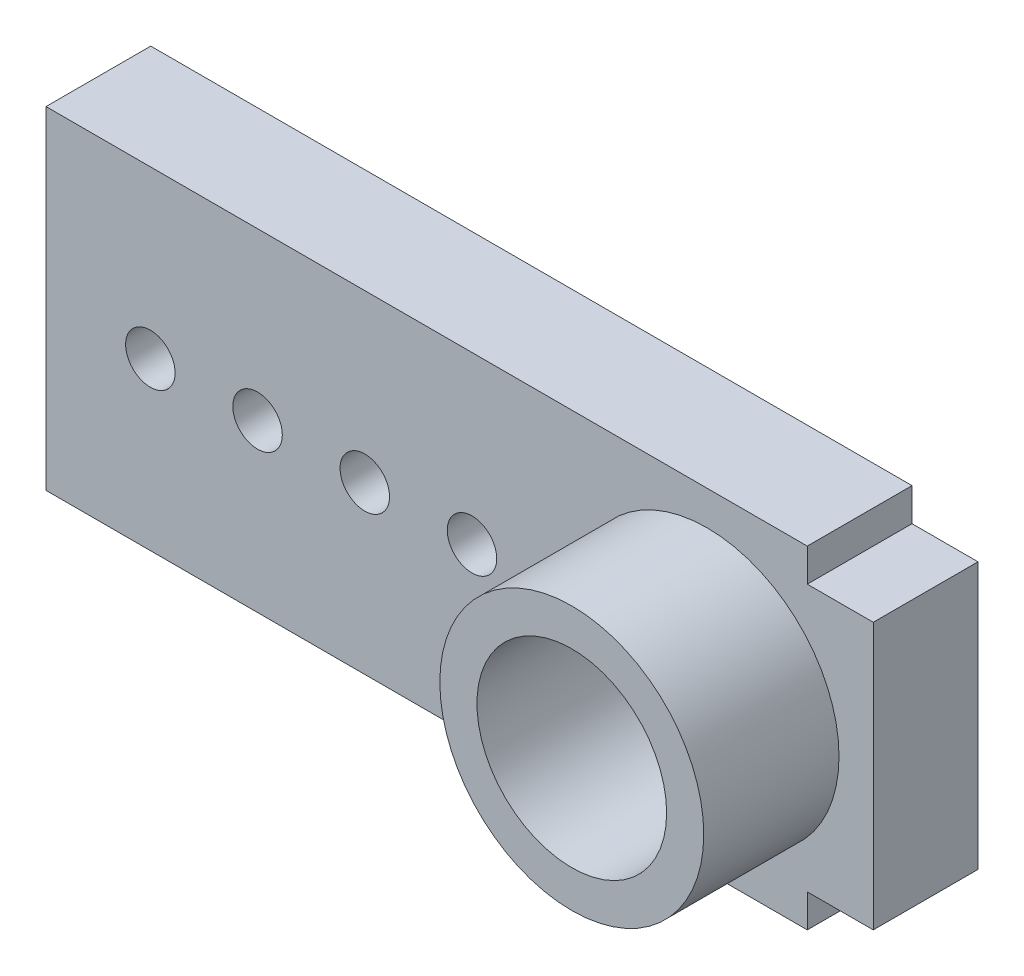
SolidWorks part; units mm, degrees
ref_plane "Front Plane" through (0, 0, 0) normal (0, 0, 1) x (1, 0, 0)
ref_plane "Top Plane" through (0, 0, 0) normal (0, 1, 0) x (1, 0, 0)
ref_plane "Right Plane" through (0, 0, 0) normal (1, 0, 0) x (0, 0, -1)
sketch "Sketch1" plane through (0, 0, 0) normal (0, 0, 1) x (1, 0, 0)
  line L0 (0, 7.125) -> (0, -7.125) construction
  line L1 (-7.125, 0) -> (7.125, 0) construction
  line L2 (0, 7.125) -> (0, 16.875) construction
  line L3 (-5.0381, 5.0381) -> (5.0381, -5.0381) construction
  line L4 (-5.0381, -5.0381) -> (5.0381, 5.0381) construction
  line L5 (-5.0381, 5.0381) -> (-5.0381, 20.0381)
  line L6 (-5.0381, 20.0381) -> (5.0381, 20.0381)
  line L7 (5.0381, 20.0381) -> (5.0381, 5.0381)
  line L8 (5.0381, 5.0381) -> (20.0381, 5.0381)
  line L9 (20.0381, 5.0381) -> (20.0381, -5.0381)
  line L10 (20.0381, -5.0381) -> (5.0381, -5.0381)
  line L11 (7.125, 0) -> (16.875, 0) construction
  line L12 (5.0381, -5.0381) -> (5.0381, -20.0381)
  line L13 (5.0381, -20.0381) -> (-5.0381, -20.0381)
  line L14 (-5.0381, -20.0381) -> (-5.0381, -5.0381)
  line L15 (0, -7.125) -> (0, -16.875) construction
  line L16 (-5.0381, -5.0381) -> (-20.0381, -5.0381)
  line L17 (-20.0381, -5.0381) -> (-20.0381, 5.0381)
  line L18 (-20.0381, 5.0381) -> (-5.0381, 5.0381)
  line L19 (-7.125, 0) -> (-16.875, 0) construction
  circle A0 centre (0, 0) radius 2.875
  circle A1 centre (0, 0) radius 7.125 construction
  circle A2 centre (0, 7.125) radius 0.75
  circle A3 centre (0, 10.375) radius 0.75
  circle A4 centre (0, 13.625) radius 0.75
  circle A5 centre (0, 16.875) radius 0.75
  circle A6 centre (7.125, 0) radius 0.75
  circle A7 centre (10.375, 0) radius 0.75
  circle A8 centre (13.625, 0) radius 0.75
  circle A9 centre (16.875, 0) radius 0.75
  circle A10 centre (0, -7.125) radius 0.75
  circle A11 centre (0, -10.375) radius 0.75
  circle A12 centre (0, -13.625) radius 0.75
  circle A13 centre (0, -16.875) radius 0.75
  circle A14 centre (-7.125, 0) radius 0.75
  circle A15 centre (-10.375, 0) radius 0.75
  circle A16 centre (-13.625, 0) radius 0.75
  circle A17 centre (-16.875, 0) radius 0.75
  point P9 (0, 10.375)
  point P11 (0, 13.625)
  point P27 (10.375, 0)
  point P29 (13.625, 0)
  point P41 (0, -10.375)
  point P43 (0, -13.625)
  point P55 (-10.375, 0)
  point P57 (-13.625, 0)
  point P67 (0, 0)
  dimension "D1" = 5.75
  dimension "D2" = 14.25
  dimension "D3" = 1.5
  dimension "D7" = 1.5
  dimension "D8" = 1.5
  dimension "D9" = 1.5
  dimension "D4" = 9.75
  dimension "D5" = 3.25
  dimension "D6" = 3.25
  dimension "D10" = 45
  dimension "D11" = 45
  dimension "D12" = 15
  dimension "D13" = 4
extrude "Boss-Extrude1" add sketch "Sketch1" along normal blind 3.175
sketch "Sketch2" plane through (0, 0, 3.175) normal (0, 0, 1) x (1, 0, 0)
  circle A0 centre (0, 0) radius 4
  circle A1 centre (0, 0) radius 2.875
  dimension "D1" = 8
  dimension "D2" = 5.75
extrude "Boss-Extrude2" add sketch "Sketch2" along normal blind 4.1
sketch "Sketch3" plane through (0, 0, 0) normal (0, 0, -1) x (-1, 0, 0)
  line L0 (-5.0381, 4.0381) -> (-5.0381, -4.0381)
  line L1 (-5.0381, 5.0381) -> (-21.0381, 5.0381)
  line L2 (-5.0381, -5.0381) -> (-21.0381, -5.0381)
  line L3 (-21.0381, 5.0381) -> (-21.0381, -5.0381)
  line L4 (-3.0381, 5.0381) -> (5.0381, 5.0381)
  line L5 (-5.0381, 5.0381) -> (-5.0381, 21.0381)
  line L6 (5.0381, 5.0381) -> (5.0381, 21.0381)
  line L7 (-5.0381, 21.0381) -> (5.0381, 21.0381)
  line L8 (-3.0381, -4.0381) -> (-3.0381, -5.0381)
  line L9 (-5.0381, -4.0381) -> (-3.0381, -4.0381)
  line L10 (-5.0381, -21.0381) -> (5.0381, -21.0381)
  line L11 (5.0381, -5.0381) -> (5.0381, -21.0381)
  line L12 (-20.0381, 0) -> (20.0381, 0) construction
  line L13 (0, 20.0381) -> (0, -20.0381) construction
  line L14 (-5.0381, 20.0381) -> (5.0381, 20.0381) construction
  line L15 (5.0381, -20.0381) -> (-5.0381, -20.0381) construction
  line L16 (-5.0381, 4.0381) -> (-3.0381, 4.0381)
  line L17 (-3.0381, 4.0381) -> (-3.0381, 5.0381)
  line L18 (-20.0381, -5.0381) -> (-20.0381, 5.0381) construction
  line L19 (20.0381, 5.0381) -> (20.0381, -5.0381) construction
  line L20 (-5.0381, -5.0381) -> (-5.0381, -21.0381)
  line L21 (-3.0381, -5.0381) -> (5.0381, -5.0381)
  dimension "D1" = 16
  dimension "D2" = 16
  dimension "D3" = 1
  dimension "D4" = 1
  dimension "D5" = 2
  dimension "D6" = 1
extrude "Cut-Extrude1" cut sketch "Sketch3" against normal through all
equation "\"circle_diameter\"=1.5"
equation "\"D3@Sketch1\"=\"circle_diameter\""
equation "\"center_to_center_dist\"=3.25"
equation "\"D5@Sketch1\"=\"center_to_center_dist\""
